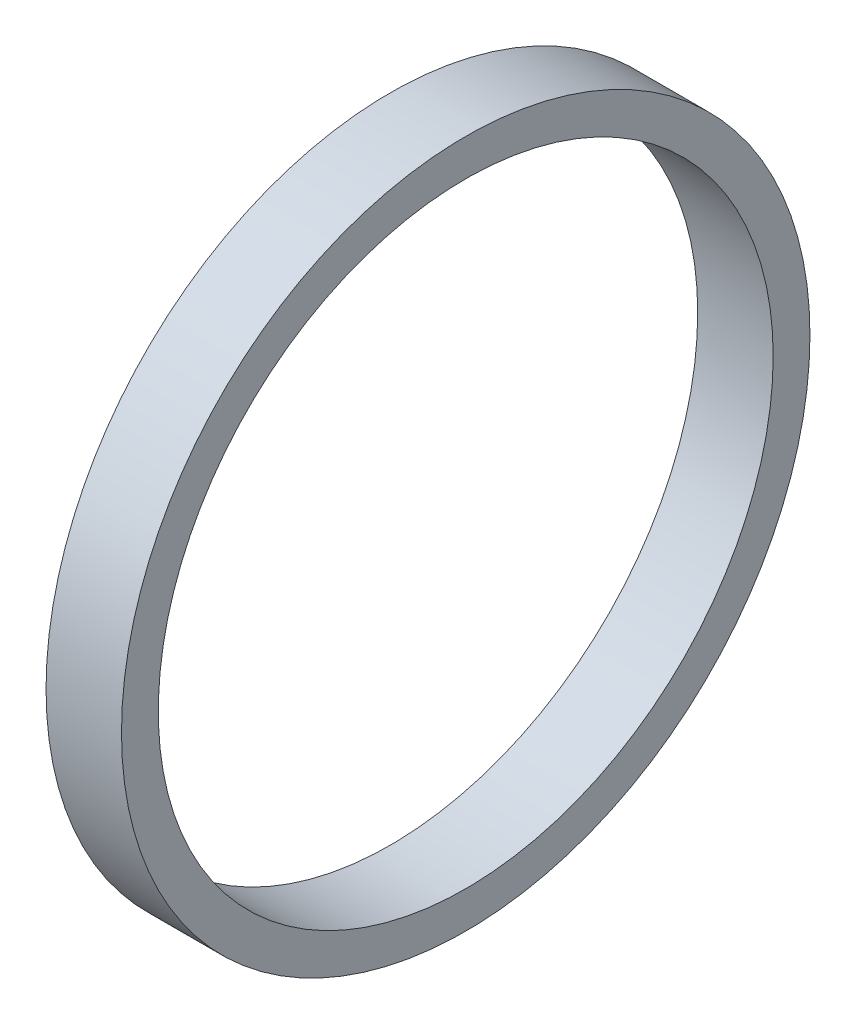
SolidWorks part; units mm, degrees
ref_plane "Front Plane" through (0, 0, 0) normal (0, 0, 1) x (1, 0, 0)
ref_plane "Top Plane" through (0, 0, 0) normal (0, 1, 0) x (1, 0, 0)
ref_plane "Right Plane" through (0, 0, 0) normal (1, 0, 0) x (0, 0, -1)
sketch "Sketch1" plane through (0, 0, 0) normal (1, 0, 0) x (0, 0, -1)
  circle A0 centre (0, 0) radius 36.5
  circle A1 centre (0, 0) radius 32.6
  dimension "D1" = 73
  dimension "D2" = 65.2
extrude "Boss-Extrude1" add sketch "Sketch1" along normal blind 8 contours A0
